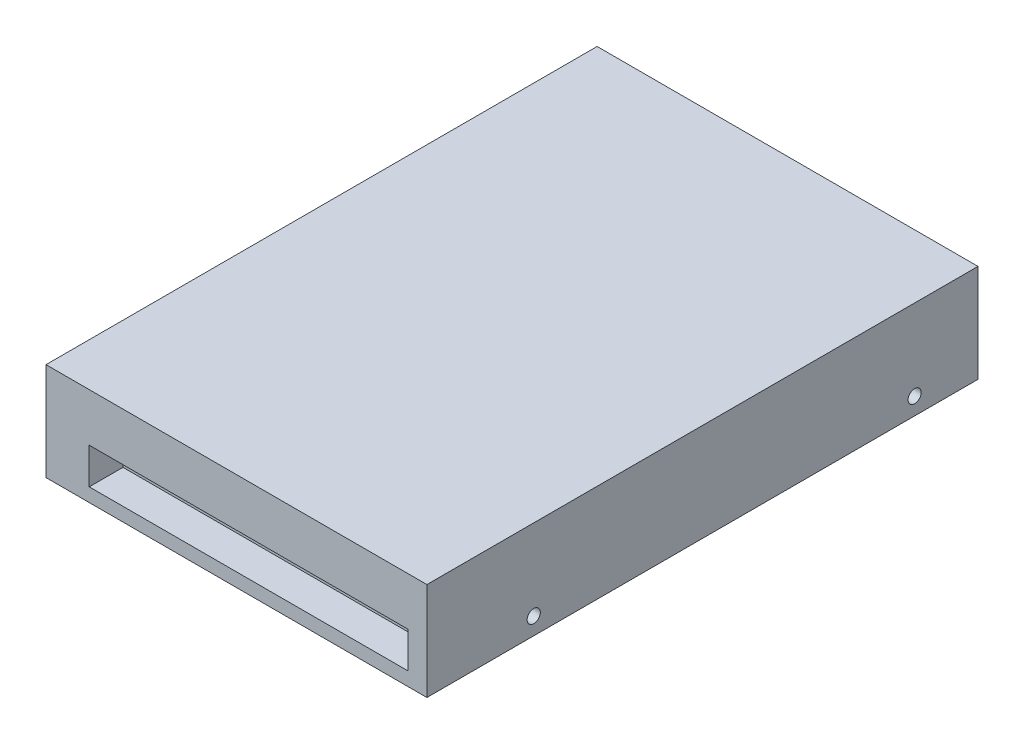
SolidWorks part; units mm, degrees
ref_plane "Přední rovina" through (0, 0, 0) normal (0, 0, 1) x (1, 0, 0)
ref_plane "Horní rovina" through (0, 0, 0) normal (0, 1, 0) x (1, 0, 0)
ref_plane "Pravá rovina" through (0, 0, 0) normal (1, 0, 0) x (0, 0, -1)
sketch "Skica1" plane through (0, 0, 0) normal (0, 1, 0) x (1, 0, 0)
  line L0 (-50.8, 73.5) -> (50.8, -73.5) construction
  line L1 (-50.8, -73.5) -> (50.8, -73.5)
  line L2 (-50.8, -73.5) -> (-50.8, 73.5)
  line L3 (-50.8, 73.5) -> (50.8, 73.5)
  line L4 (50.8, -73.5) -> (50.8, 73.5)
  dimension "D1" = 101.6
  dimension "D2" = 147
extrude "Přidat vysunutím1" add sketch "Skica1" along normal blind 26.1
sketch "Skica3" plane through (0, 0, 73.5) normal (0, 0, 1) x (1, 0, 0)
  line L1 (-39.2682, 3.6375) -> (45.7946, 3.6375)
  line L2 (-39.2682, 3.6375) -> (-39.2682, 13.2595)
  line L3 (-39.2682, 13.2595) -> (45.7946, 13.2595)
  line L4 (45.7946, 3.6375) -> (45.7946, 13.2595)
extrude "Odebrat vysunutím2" cut sketch "Skica3" against normal blind 9
sketch "Skica2" plane through (0, 0, 0) normal (0, -1, 0) x (1, 0, 0)
  line L0 (-50.8, 73.5) -> (50.8, 73.5) construction
  line L1 (-50.8, -73.5) -> (-50.8, 73.5) construction
  circle A0 centre (-47.62, 32.22) radius 1.7526
  circle A1 centre (-47.62, -12.23) radius 1.7526
  circle A2 centre (-47.62, -43.98) radius 1.7526
  dimension "D1" = 41.28
  dimension "D2" = 44.45
  dimension "D3" = 76.2
  dimension "D4" = 3.5052
  dimension "D5" = 3.18
extrude "Odebrat vysunutím1" cut sketch "Skica2" against normal blind 5
sketch "Skica4" plane through (-50.8, 0, 0) normal (-1, 0, 0) x (0, 0, 1)
  line L0 (73.5, 26.1) -> (73.5, 0) construction
  circle A0 centre (45, 4.5674) radius 1.7526
  circle A2 centre (-56.6, 4.5674) radius 1.7526
  dimension "D2" = 101.6
  dimension "D3" = 3.5052
  dimension "D1" = 28.5
extrude "Odebrat vysunutím3" cut sketch "Skica4" against normal blind 5
mirror "Zrcadlit1" about plane through (0, 0, 0) normal (1, 0, 0) of "Odebrat vysunutím3", "Odebrat vysunutím1"
